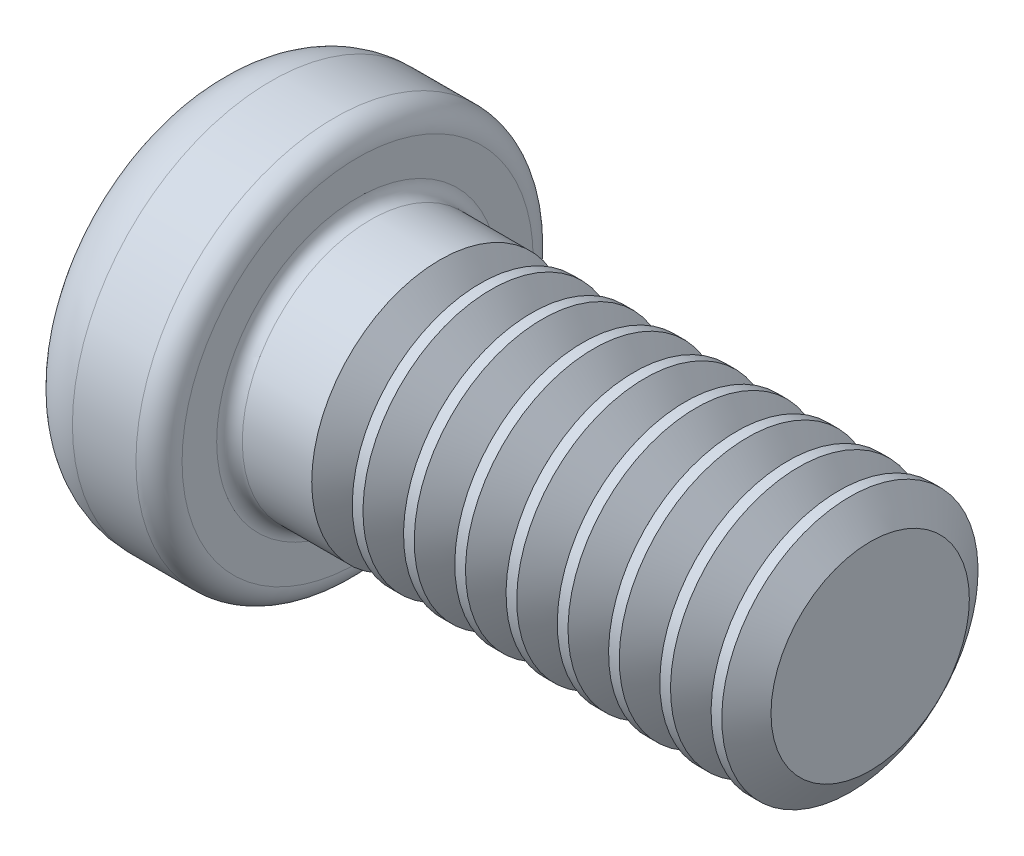
SolidWorks part; units mm, degrees
material "Aço NB 1045"
ref_plane "Plane1" through (0, 0, 0) normal (0, 0, 1) x (1, 0, 0)
ref_plane "Plane2" through (0, 0, 0) normal (0, 1, 0) x (1, 0, 0)
ref_plane "Plane3" through (0, 0, 0) normal (1, 0, 0) x (0, 0, -1)
sketch "BodySke" plane through (0, 0, 0) normal (0, 0, 1) x (1, 0, 0)
  line L0 (1.3, 1) -> (1.3, 1.37)
  line L1 (1.5, 6.35) -> (1.5, -3.175) construction
  line L2 (-25.4, 0) -> (127, 0) construction
  line L3 (5.3, 0) -> (0, 0)
  line L4 (1.3, 1) -> (5.3, 1)
  line L5 (5.3, 1) -> (5.3, 0)
  line L6 (0.6242, 1.55) -> (1.12, 1.55)
  line L8 (1.3, 6.35) -> (1.3, -3.175) construction
  arc A0 (0.138, 1.1667) -> (0, 0) centre (5, 0) ccw
  arc A1 (1.3, 1.37) -> (1.12, 1.55) centre (1.12, 1.37) ccw
  arc A2 (0.138, 1.1667) -> (0.6242, 1.55) centre (0.6242, 1.05) cw
  point P18 (1.3, 1.55)
  dimension "Head_crown_rad" = 5
  dimension "Head_fillet_rad" = 0.5
  dimension "D1" = 0.18
  dimension "Length" = 4
  dimension "Head_ht" = 1.3
  dimension "Head_dia" = 3.1
  dimension "Advance" = 0.4
  dimension "Thread_nom" = 4
  dimension "Diameter" = 2
revolve "Base-Revolve" add sketch "BodySke"
cosmetic thread "ThreadCosmetic" [suppressed]
fillet "Fillet1" radius 0.1 1 edges at (1.3, 0, 1)
sketch "Sketch3" plane through (0, 0, 0) normal (1, 0, 0) x (0, 0, -1)
  line L0 (0.24, -1.05) -> (-0.24, -1.05)
  line L1 (0.24, -1.05) -> (0.24, 1.05)
  line L2 (-0.24, 1.05) -> (0.24, 1.05)
  line L3 (-0.24, 1.05) -> (-0.24, -1.05)
  dimension "Cross_dia" = 2.1
  dimension "D1" = 1.05
  dimension "Cross_width" = 0.48
  dimension "D2" = 0.24
ref_plane "Plane4" through (1.42, 0, 0) normal (1, 0, 0) x (0, 0, -1)
sketch "Sketch4" plane through (1.42, 0, 0) normal (1, 0, 0) x (0, 0, -1)
  line L0 (0.24, -0.342) -> (-0.24, -0.342)
  line L1 (0.24, -0.342) -> (0.24, 0.342)
  line L2 (-0.24, 0.342) -> (0.24, 0.342)
  line L3 (-0.24, 0.342) -> (-0.24, -0.342)
  dimension "D1" = 0.48
  dimension "D2" = 0.684
  dimension "D3" = 0.24
  dimension "D4" = 0.342
loft "Recess" cut profiles "Sketch3", "Sketch4"
pattern_circular "RecPat" count 2 every 90 about axis through (0, 0, 0) along (1, 0, 0) of "Recess"
sketch "RecCorSke" plane through (0, 0, 0) normal (0, 0, 1) x (1, 0, 0)
  line L0 (-3.175, 0) -> (15.875, 0) construction
  line L1 (-25.4, 0) -> (127, 0) construction
  line L2 (0, 0) -> (0, 0.4548)
  line L3 (0, 0.4548) -> (1.42, 0.3555)
  line L4 (1.42, 0.3555) -> (1.5355, 0)
  line L5 (1.5355, 0) -> (0, 0)
  dimension "Diameter" = 0.711
  dimension "Depth" = 1.42
  dimension "Draft_angle" = 4
  dimension "Bottom_angle" = 18
revolve "RecessCore" cut sketch "RecCorSke" angle 360 about L0
sketch "ThdSchSke" plane through (0, 0, 0) normal (0, 0, 1) x (1, 0, 0)
  line L0 (2.1, -0.774) -> (1.9418, -1)
  line L1 (2.1, -0.774) -> (2.2582, -1)
  line L2 (2.2582, -1) -> (2.2582, -1.25)
  line L3 (-3.175, 0) -> (5.1513, 0) construction
  line L5 (2.2582, -1.25) -> (1.9418, -1.25)
  line L6 (1.9418, -1.25) -> (1.9418, -1)
  dimension "Diameter" = 2
  dimension "SideAngle" = 55
  dimension "VeeAngle" = 70
  dimension "Thread_minor" = 1.548
  dimension "Overcut" = 2.5
  dimension "Start" = 2.1
revolve "ThreadSchematic" cut sketch "ThdSchSke" angle 360 about L3
pattern_linear "ThdSchPat" count 9 spacing 0.4 along (1, 0, 0) of "ThreadSchematic"
equation "\"D1@Sketch3\" = \"Cross_dia@Sketch3\" / 2"
equation "\"D2@Sketch3\" = \"Cross_width@Sketch3\" / 2"
equation "\"Depth@RecCorSke\" = \"Cross_depth@Plane4\""
equation "\"D1@Sketch4\" = \"Cross_width@Sketch3\""
equation "\"D2@Sketch4\" = \"Cross_dia@Sketch3\" - 2.0 * \"Cross_depth@Plane4\" * tan(26.5  * 0.017453292)"
equation "\"D3@Sketch4\" = \"D1@Sketch4\" / 2"
equation "\"D4@Sketch4\" = \"D2@Sketch4\" / 2"
equation "\"Thread_length@ThreadCosmetic\" = ((sgn( (\"Length@BodySke\" - \"Advance@BodySke\" * 2.0 ) - \"Thread_nom@BodySke\" )-1)*( (\"Length@BodySke\" - \"Advance@BodySke\" * 2.0 ) - \"Thread_nom@BodySke\" ))/-2+ \"Thread_nom@BodySke\""
equation "\"Thread_minor@ThdSchSke\" = \"Thread_minor@ThreadCosmetic\""
equation "\"Diameter@ThdSchSke\" = \"Diameter@BodySke\""
equation "\"Overcut@ThdSchSke\" = \"Diameter@BodySke\" * 1.25"
equation "\"Start@ThdSchSke\" = \"Head_ht@BodySke\" + \"Length@BodySke\" - \"Thread_length@ThreadCosmetic\"  '---Non-countersunk---"
equation "\"Num_threads@ThdSchPat\" = int( \"Thread_length@ThreadCosmetic\" / \"Advance@BodySke\" + 0.999 )  + 1"
equation "\"Advance@ThdSchPat\" = \"Thread_length@ThreadCosmetic\" /  (\"Num_threads@ThdSchPat\" - 1) 'relax it"
